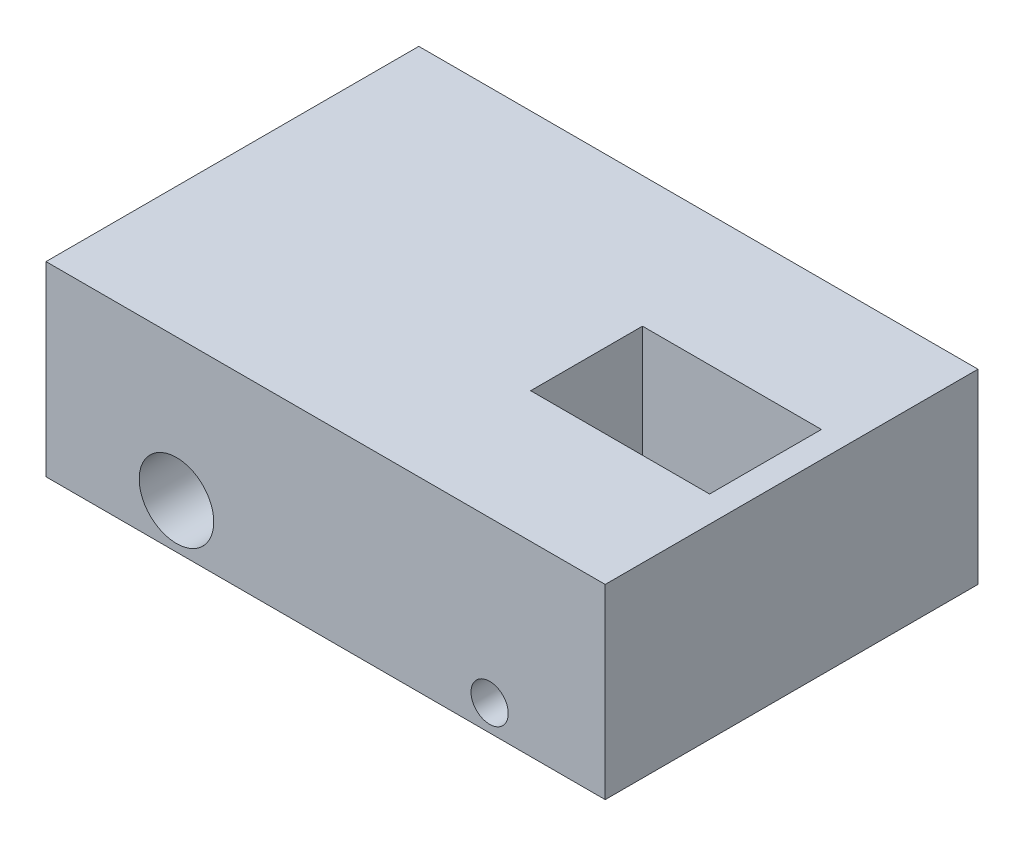
SolidWorks part; units mm, degrees
ref_plane "Plan de face" through (0, 0, 0) normal (0, 0, 1) x (1, 0, 0)
ref_plane "Plan de dessus" through (0, 0, 0) normal (0, 1, 0) x (1, 0, 0)
ref_plane "Plan de droite" through (0, 0, 0) normal (1, 0, 0) x (0, 0, -1)
sketch "Sketch1" plane through (0, 0, 0) normal (0, 1, 0) x (1, 0, 0)
  line L1 (-75, 50) -> (75, 50)
  line L2 (-75, 50) -> (-75, -50)
  line L3 (-75, -50) -> (75, -50)
  line L4 (75, 50) -> (75, -50)
  point P4 (-75, 0)
  dimension "D1" = 150
  dimension "D2" = 100
  dimension "D3" = 75
  dimension "D4" = 50
extrude "Boss-Extrude1" add sketch "Sketch1" along normal blind 50
sketch "Sketch3" plane through (0, 0, 50) normal (0, 0, 1) x (1, 0, 0)
  line L0 (-75, 0) -> (75, 0) construction
  circle A0 centre (-40, 12) radius 10
  dimension "D3" = 20
  dimension "D1" = 12
  dimension "D2" = 40
extrude "Cut-Extrude1" cut sketch "Sketch3" against normal blind 100
sketch "Sketch4" plane through (0, 0, 0) normal (0, -1, 0) x (1, 0, 0)
  line L1 (20, 15) -> (68, 15)
  line L2 (20, 15) -> (20, -15)
  line L3 (20, -15) -> (68, -15)
  line L4 (68, 15) -> (68, -15)
  dimension "D1" = 30
  dimension "D2" = 48
  dimension "D3" = 20
  dimension "D4" = 15
extrude "Cut-Extrude2" cut sketch "Sketch4" against normal blind 100
sketch "Sketch5" plane through (0, 0, 15) normal (0, 0, -1) x (-1, 0, 0)
  line L0 (-75, 50) -> (75, 50) construction
  line L1 (-68, 50) -> (-68, 0) construction
  circle A0 centre (-44, 7) radius 5
  dimension "D1" = 10
  dimension "D2" = 43
  dimension "D3" = 24
extrude "Cut-Extrude3" cut sketch "Sketch5" against normal through all and the other way through all
